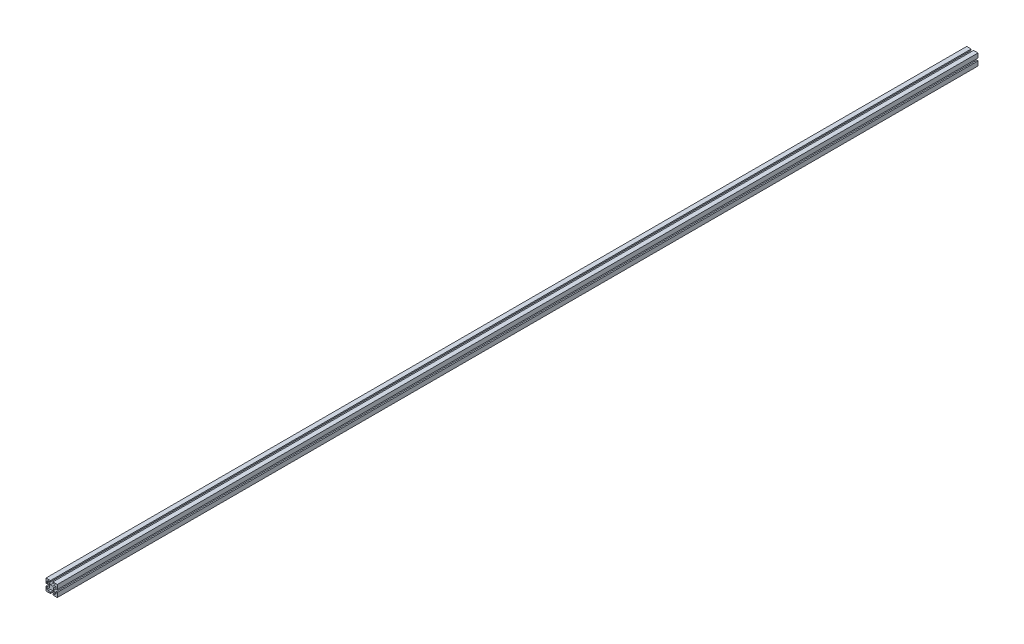
SolidWorks part; units mm, degrees
ref_plane "Front Plane" through (0, 0, 0) normal (0, 0, 1) x (1, 0, 0)
ref_plane "Top Plane" through (0, 0, 0) normal (0, 1, 0) x (1, 0, 0)
ref_plane "Right Plane" through (0, 0, 0) normal (1, 0, 0) x (0, 0, -1)
sketch "Sketch2" plane through (0.5947, -0.5947, 0) normal (0, 0, 1) x (1, 0, 0)
  line L0 (-0.5947, 0.5947) -> (-0.5947, 20.2394) construction
  line L1 (-0.5947, 0.5947) -> (-20.2394, 0.5947) construction
  line L2 (-0.5947, 0.5947) -> (-20.2394, 20.2394) construction
  line L3 (-19.6447, 19.6447) -> (-4.6587, 19.6447)
  line L4 (-4.6587, 19.6447) -> (-4.6587, 15.5807)
  line L5 (-4.6587, 15.5807) -> (-12.707, 15.5807)
  line L6 (-12.707, 15.5807) -> (-4.4774, 7.3511)
  line L7 (-4.4774, 7.3511) -> (3.288, 7.3511)
  line L8 (-19.6447, 19.6447) -> (-19.6447, 4.6587)
  line L9 (-19.6447, 4.6587) -> (-15.5807, 4.6587)
  line L10 (-15.5807, 4.6587) -> (-15.5807, 12.707)
  line L11 (-15.5807, 12.707) -> (-7.3511, 4.4774)
  line L12 (-7.3511, 4.4774) -> (-7.3511, -3.288)
  line L13 (-4.4774, -6.1617) -> (3.288, -6.1617)
  line L14 (-12.707, -14.3913) -> (-4.4774, -6.1617)
  line L15 (-4.6587, -14.3913) -> (-12.707, -14.3913)
  line L16 (-4.6587, -18.4553) -> (-4.6587, -14.3913)
  line L17 (-19.6447, -18.4553) -> (-4.6587, -18.4553)
  line L18 (-19.6447, -18.4553) -> (-19.6447, -3.4693)
  line L19 (-19.6447, -3.4693) -> (-15.5807, -3.4693)
  line L20 (-15.5807, -3.4693) -> (-15.5807, -11.5176)
  line L21 (-15.5807, -11.5176) -> (-7.3511, -3.288)
  line L22 (11.5176, 15.5807) -> (3.288, 7.3511)
  line L23 (3.4693, 15.5807) -> (11.5176, 15.5807)
  line L24 (3.4693, 19.6447) -> (3.4693, 15.5807)
  line L25 (18.4553, 19.6447) -> (3.4693, 19.6447)
  line L26 (18.4553, 19.6447) -> (18.4553, 4.6587)
  line L27 (18.4553, 4.6587) -> (14.3913, 4.6587)
  line L28 (14.3913, 4.6587) -> (14.3913, 12.707)
  line L29 (14.3913, 12.707) -> (6.1617, 4.4774)
  line L30 (6.1617, 4.4774) -> (6.1617, -3.288)
  line L31 (14.3913, -11.5176) -> (6.1617, -3.288)
  line L32 (14.3913, -3.4693) -> (14.3913, -11.5176)
  line L33 (18.4553, -3.4693) -> (14.3913, -3.4693)
  line L34 (18.4553, -18.4553) -> (18.4553, -3.4693)
  line L35 (18.4553, -18.4553) -> (3.4693, -18.4553)
  line L36 (3.4693, -18.4553) -> (3.4693, -14.3913)
  line L37 (3.4693, -14.3913) -> (11.5176, -14.3913)
  line L38 (11.5176, -14.3913) -> (3.288, -6.1617)
  point P26 (-7.3511, 0.5947)
  point P27 (-0.5947, 7.3511)
  point P44 (-0.5947, -6.1617)
  dimension "D1" = 38.1
  dimension "D2" = 8.128
  dimension "D3" = 13.5128
  dimension "D4" = 4.064
  dimension "D5" = 4.064
extrude "Boss-Extrude1" add sketch "Sketch2" along normal blind 3100.3875
other "1515<1>"
